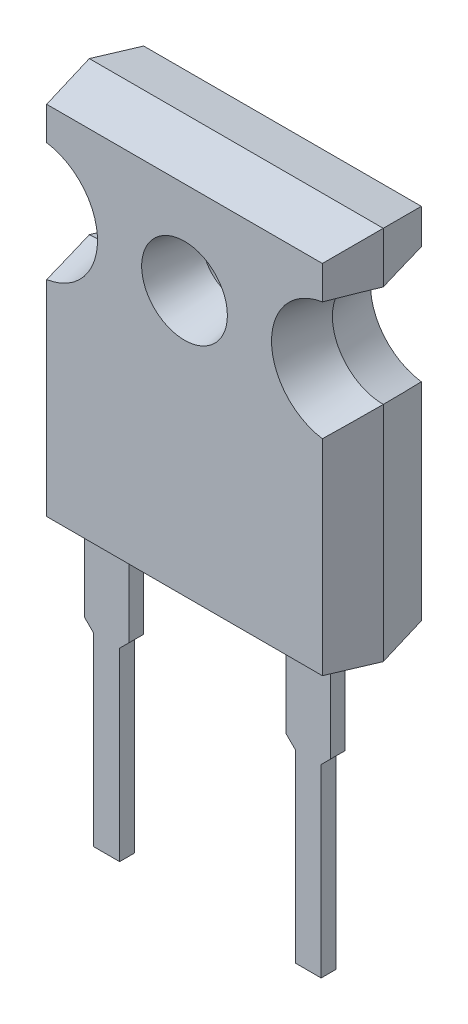
SolidWorks part; units mm, degrees
ref_plane "Plano frontal" through (0, 0, 0) normal (0, 0, 1) x (1, 0, 0)
ref_plane "Plano superior" through (0, 0, 0) normal (0, 1, 0) x (1, 0, 0)
ref_plane "Plano direito" through (0, 0, 0) normal (1, 0, 0) x (0, 0, -1)
sketch "Esboço1" plane through (0, 0, 0) normal (0, 0, 1) x (1, 0, 0)
  line L0 (-24.0663, -3.4129) -> (-24.0663, 8.6371)
  line L1 (-24.0663, 14.1371) -> (-24.0663, 16.8871)
  line L2 (-24.0663, 16.8871) -> (-8.1663, 16.8871)
  line L3 (-8.1663, 16.8871) -> (-8.1663, 14.1371)
  line L4 (-8.1663, 8.6371) -> (-8.1663, -3.4129)
  line L5 (-8.1663, -3.4129) -> (-24.0663, -3.4129)
  line L6 (-16.1163, 16.8871) -> (-16.1163, -3.4129) construction
  line L7 (-24.0663, 11.3871) -> (-8.1663, 11.3871) construction
  arc A0 (-24.0663, 8.6371) -> (-24.0663, 14.1371) centre (-24.0663, 11.3871) ccw
  arc A1 (-8.1663, 14.1371) -> (-8.1663, 8.6371) centre (-8.1663, 11.3871) ccw
  circle A2 centre (-16.1163, 11.3871) radius 1.825
  dimension "D4" = 2.75
  dimension "D5" = 3.65
  dimension "D1" = 20.3
  dimension "D2" = 15.9
  dimension "D3" = 5.5
extrude "Ressalto-extrusão1" add sketch "Esboço1" along normal blind 2.8 draft 10 and the other way blind 2.5 draft 10
ref_plane "Plano1" through (0, 0, 0.9) normal (0, 0, -1) x (-1, 0, 0)
sketch "Esboço2" plane through (0, 0, 0.9) normal (0, 0, -1) x (-1, 0, 0)
  line L0 (16.1163, -3.4129) -> (16.1163, -19.3537) construction
  line L1 (24.0663, -3.4129) -> (8.1663, -3.4129) construction
  line L2 (22.6264, -3.4129) -> (20.2264, -3.4129)
  line L3 (20.2264, -3.4129) -> (20.2264, -7.7129)
  line L4 (20.2264, -7.7129) -> (20.7264, -8.2129)
  line L5 (20.7264, -8.2129) -> (20.7264, -18.2129)
  line L6 (20.7264, -18.2129) -> (22.1264, -18.2129)
  line L7 (22.1264, -18.2129) -> (22.1264, -8.2129)
  line L8 (22.1264, -8.2129) -> (22.6264, -7.7129)
  line L9 (22.6264, -7.7129) -> (22.6264, -3.4129)
  line L10 (21.4264, -3.4129) -> (21.4264, -18.2129) construction
  dimension "D1" = 1.4
  dimension "D2" = 0.7
  dimension "D3" = 2.4
  dimension "D4" = 4.3
  dimension "D5" = 14.8
  dimension "D6" = 14.8
extrude "Ressalto-extrusão2" add sketch "Esboço2" against normal blind 0.8 separate body
pattern_linear "Padrão linear3" count 2 spacing 10.9 along (1, 0, 0) of bodies 105
ref_plane "Plano2" through (0, 0, 2.9) normal (0, 0, -1) x (-1, 0, 0)
